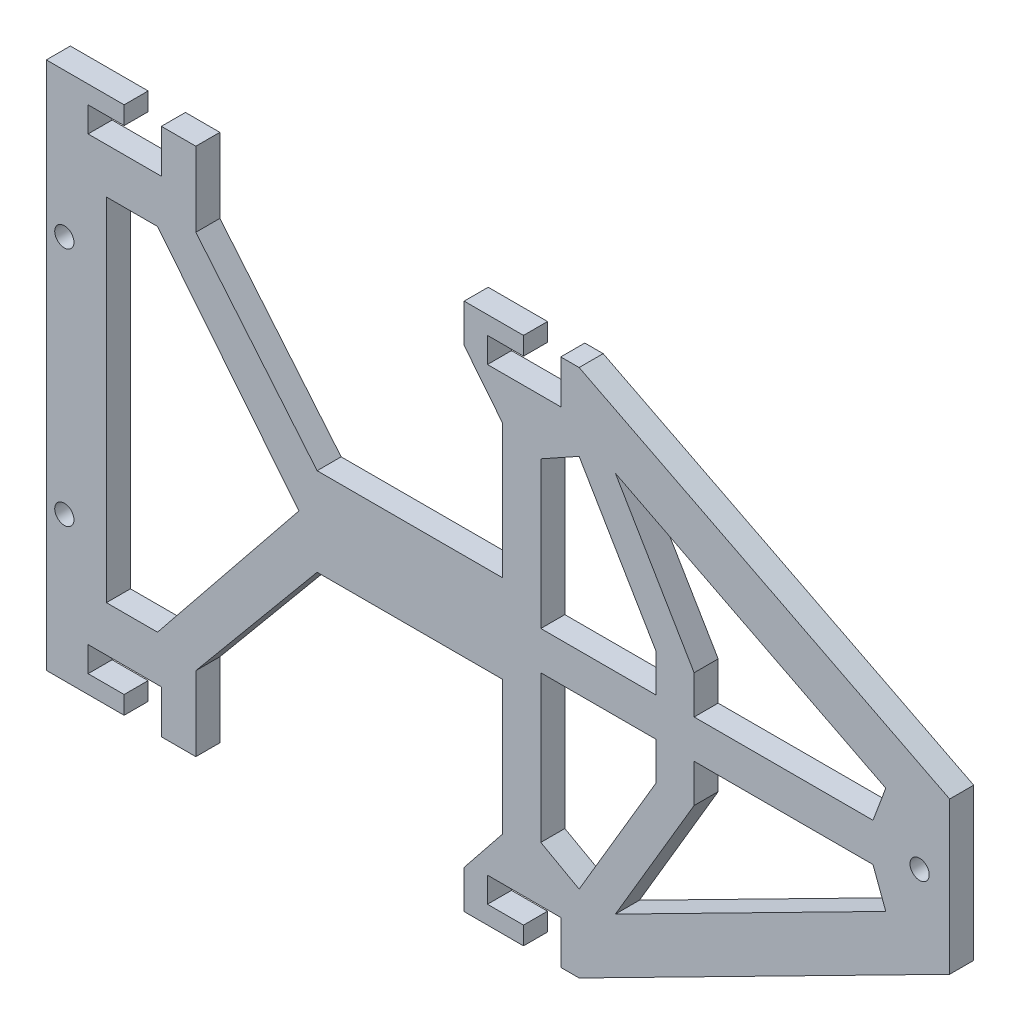
SolidWorks part; units mm, degrees
ref_plane "前视基准面" through (0, 0, 0) normal (0, 0, 1) x (1, 0, 0)
ref_plane "上视基准面" through (0, 0, 0) normal (0, 1, 0) x (1, 0, 0)
ref_plane "右视基准面" through (0, 0, 0) normal (1, 0, 0) x (0, 0, -1)
sketch "草图2" plane through (0, 0, 0) normal (0, 0, 1) x (1, 0, 0)
  line L0 (31.3671, 4.4417) -> (30.3038, 1.5949)
  line L1 (30.3038, -1.5949) -> (31.3671, -4.4417)
  line L2 (30.3038, 1.5949) -> (15.4177, 1.5949)
  line L3 (15.4177, -1.5949) -> (30.3038, -1.5949)
  line L4 (31.3671, -4.4417) -> (8.8661, -15.8862)
  line L5 (8.8661, -15.8862) -> (15.4177, -4.7848)
  line L6 (15.4177, -4.7848) -> (15.4177, -1.5949)
  line L7 (15.4177, 1.5949) -> (15.4177, 4.7848)
  line L8 (8.8661, 15.8862) -> (31.3671, 4.4417)
  line L9 (15.4177, 4.7848) -> (8.8661, 15.8862)
  line L10 (5.8481, -15.5949) -> (2.6582, -13.8228)
  line L11 (12.2278, -4.7848) -> (5.8481, -15.5949)
  line L12 (2.6582, -13.8228) -> (2.6582, -1.5949)
  line L13 (12.2278, 1.5949) -> (2.6582, 1.5949)
  line L14 (2.6582, -1.5949) -> (12.2278, -1.5949)
  line L15 (-26.0506, -22) -> (-26.0506, -15.7967)
  line L16 (-28.9181, -22) -> (-26.0506, -22)
  line L17 (-28.9181, -18.4) -> (-28.9181, -22)
  line L18 (-35.0181, -18.4) -> (-28.9181, -18.4)
  line L19 (-32.0181, -22) -> (-32.0181, -20.5)
  line L20 (-38.4941, -22) -> (-32.0181, -22)
  line L21 (-38.4941, 22) -> (-38.4941, -22)
  line L22 (-32.0181, 22) -> (-38.4941, 22)
  line L23 (-32.0181, 20.5) -> (-32.0181, 22)
  line L24 (-28.9181, 18.4) -> (-35.0181, 18.4)
  line L25 (-28.9181, 22) -> (-28.9181, 18.4)
  line L26 (-26.0506, 22) -> (-28.9181, 22)
  line L27 (-26.0506, 15.7967) -> (-26.0506, 22)
  line L28 (-15.9572, 3.6582) -> (-26.0506, 15.7967)
  line L29 (-0.5316, 3.6582) -> (-15.9572, 3.6582)
  line L30 (-0.5316, 14.8228) -> (-0.5316, 3.6582)
  line L31 (-3.7215, 18.8101) -> (-0.5316, 14.8228)
  line L32 (-3.7215, 22) -> (-3.7215, 18.8101)
  line L33 (1.2188, 22) -> (-3.7215, 22)
  line L34 (1.2188, 20.5) -> (1.2188, 22)
  line L35 (4.3188, 18.4) -> (-1.7812, 18.4)
  line L36 (4.3188, 22) -> (4.3188, 18.4)
  line L37 (5.8481, 22) -> (4.3188, 22)
  line L38 (36.6835, 6.3165) -> (5.8481, 22)
  line L39 (36.6835, 0) -> (36.6835, 6.3165)
  line L43 (36.6835, -6.3165) -> (36.6835, 0)
  line L44 (5.8481, -22) -> (36.6835, -6.3165)
  line L45 (4.3188, -22) -> (5.8481, -22)
  line L46 (4.3188, -18.4) -> (4.3188, -22)
  line L47 (-1.7812, -18.4) -> (4.3188, -18.4)
  line L48 (1.2188, -22) -> (1.2188, -20.5)
  line L49 (-3.7215, -22) -> (1.2188, -22)
  line L50 (-3.7215, -18.8101) -> (-3.7215, -22)
  line L51 (-0.5316, -14.8228) -> (-3.7215, -18.8101)
  line L52 (-0.5316, -3.6582) -> (-0.5316, -14.8228)
  line L53 (-15.9572, -3.6582) -> (-0.5316, -3.6582)
  line L54 (-26.0506, -15.7967) -> (-15.9572, -3.6582)
  line L55 (12.2278, -1.5949) -> (12.2278, -4.7848)
  line L56 (12.2278, 4.7848) -> (12.2278, 1.5949)
  line L57 (5.8481, 15.5949) -> (12.2278, 4.7848)
  line L58 (2.6582, 13.8228) -> (5.8481, 15.5949)
  line L59 (2.6582, 1.5949) -> (2.6582, 13.8228)
  line L60 (-17.475, 0) -> (-29.2405, -14.6203)
  line L61 (-29.2405, -14.6203) -> (-33.4937, -14.6203)
  line L62 (-29.2405, 14.6203) -> (-17.475, 0)
  line L63 (-33.4937, 14.6203) -> (-29.2405, 14.6203)
  line L64 (-33.4937, -14.6203) -> (-33.4937, 14.6203)
  line L65 (0, 0) -> (40.4332, 0) construction
  line L66 (-32.0181, 20.5) -> (-35.0181, 20.5)
  line L67 (-35.0181, 20.5) -> (-35.0181, 18.4)
  line L68 (-32.0181, -20.5) -> (-35.0181, -20.5)
  line L69 (-35.0181, -20.5) -> (-35.0181, -18.4)
  line L70 (1.2188, 20.5) -> (-1.7812, 20.5)
  line L71 (-1.7812, 20.5) -> (-1.7812, 18.4)
  line L72 (1.2188, -20.5) -> (-1.7812, -20.5)
  line L73 (-1.7812, -20.5) -> (-1.7812, -18.4)
  dimension "D3" = 2.1
  dimension "D1" = 44
  dimension "D2" = 1.5
  dimension "D4" = 3.1
  dimension "D5" = 3
  dimension "D6" = 3
  dimension "D7" = 3.1
  dimension "D8" = 2.1
  dimension "D9" = 3.1
extrude "凸台-拉伸2" add sketch "草图2" along normal blind 2
hole_wizard "M2 螺纹孔1" positions "草图7" profile "草图6" tap size "M2" standard "GB"
sketch "草图7" plane through (0, 0, 2) normal (0, 0, 1) x (1, 0, 0)
  line L0 (0, 0) -> (-25.5852, 0) construction
  line L1 (-38.4941, 22) -> (-38.4941, -22) construction
  line L2 (36.6835, -6.3165) -> (36.6835, 6.3165) construction
  point P0 (-36.9941, 10)
  point P2 (-36.9941, -10)
  point P13 (34.1835, 0)
  dimension "D1" = 20
  dimension "D2" = 1.5
  dimension "D3" = 2.5
sketch "草图6" plane through (-36.9941, 10, 2) normal (1, 0, 0) x (0, -1, 0)
  line L0 (0, 0) -> (0, 5.6807)
  line L1 (0, 5.6807) -> (0.8, 5.2)
  line L2 (0.8, 5.2) -> (0.8, 0)
  line L5 (0.8, 0) -> (0, 0)
  line L10 (0, 5.6807) -> (-0.8, 5.2) construction
  line L11 (0, -6.35) -> (0, 107.95) construction
  dimension "螺纹孔钻头直径" = 1.6
  dimension "螺纹孔钻头深度" = 5.2
  dimension "导头角度" = 118
cosmetic thread "孔螺蚊线3" parameters "D1"=2, "D2"=2
cosmetic thread "孔螺蚊线4" parameters "D1"=2, "D2"=2
cosmetic thread "孔螺蚊线5" parameters "D1"=2, "D2"=2
